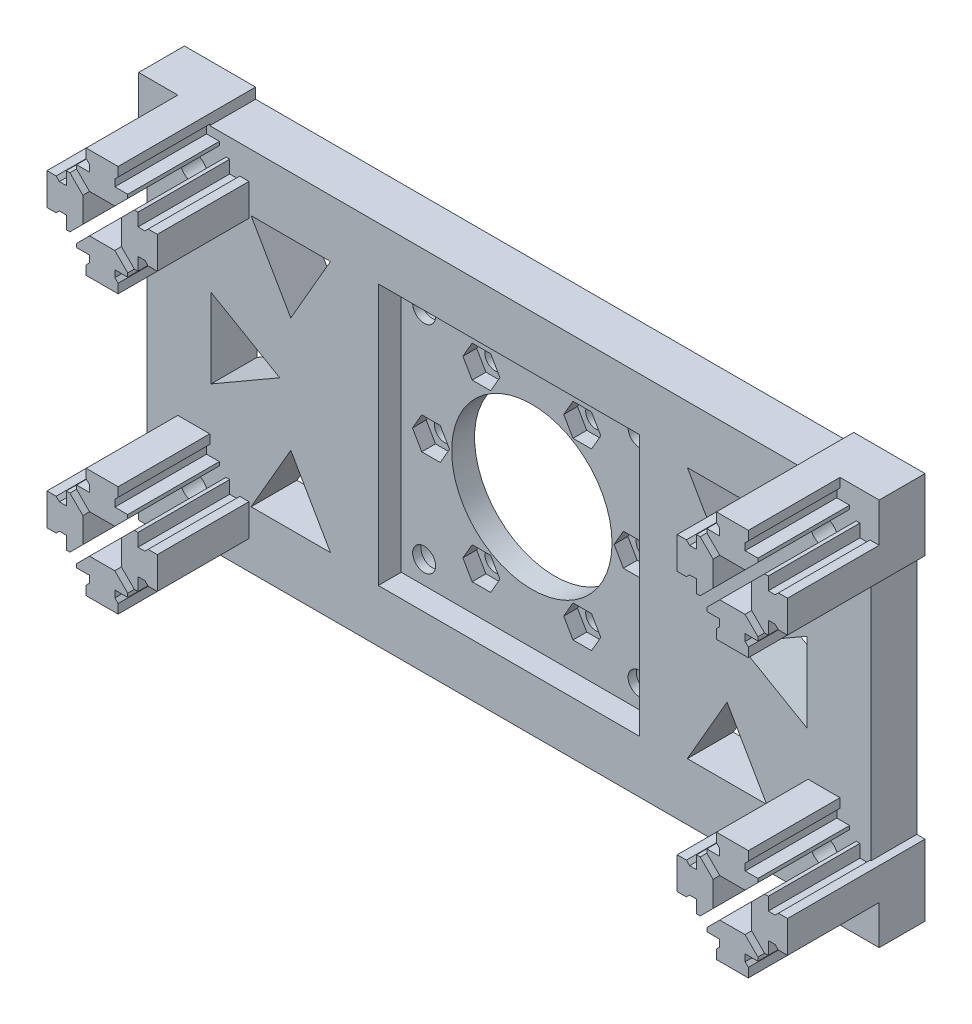
SolidWorks part; units mm, degrees
ref_plane "Plan de face" through (0, 0, 0) normal (0, 0, 1) x (1, 0, 0)
ref_plane "Plan de dessus" through (0, 0, 0) normal (0, 1, 0) x (1, 0, 0)
ref_plane "Plan de droite" through (0, 0, 0) normal (1, 0, 0) x (0, 0, -1)
sketch "Esquisse1" plane through (0, 0, 0) normal (0, 0, 1) x (1, 0, 0)
  line L0 (0, 0) -> (22, 0) construction
  line L1 (0, 0) -> (11, -19.0526) construction
  line L2 (0, 0) -> (-11, -19.0526) construction
  line L3 (0, 0) -> (-22, 0) construction
  line L4 (0, 0) -> (-11, 19.0526) construction
  line L5 (0, 0) -> (11, 19.0526) construction
  line L6 (-23.5, 21.05) -> (-23.5, 23.55)
  line L7 (23.5, -23.55) -> (21, -23.55)
  line L8 (23.5, -23.55) -> (23.5, -21.05)
  line L9 (23.5, 23.55) -> (21, 23.55)
  line L10 (-23.5, -23.55) -> (-23.5, -21.05)
  line L11 (23.5, -23.55) -> (-23.5, 23.55) construction
  line L12 (23.5, 23.55) -> (-23.5, -23.55) construction
  line L13 (-21, 23.55) -> (-23.5, 23.55)
  line L14 (23.5, 21.05) -> (23.5, 23.55)
  line L15 (-21, -23.55) -> (-23.5, -23.55)
  line L17 (79, -40) -> (-79, -40)
  line L18 (79, -40) -> (79, 40)
  line L19 (79, 40) -> (-79, 40)
  line L20 (-79, -40) -> (-79, 40)
  line L21 (79, -40) -> (-79, 40) construction
  line L22 (79, 40) -> (-79, -40) construction
  circle A0 centre (22, 0) radius 2.25
  circle A1 centre (11, -19.0526) radius 2.25
  circle A2 centre (-11, -19.0526) radius 2.25
  circle A3 centre (-22, 0) radius 2.25
  circle A4 centre (-11, 19.0526) radius 2.25
  circle A5 centre (11, 19.0526) radius 2.25
  circle A6 centre (-23.5, 23.55) radius 2.5
  circle A7 centre (23.5, 23.55) radius 2.5
  circle A8 centre (23.5, -23.55) radius 2.5
  circle A9 centre (-23.5, -23.55) radius 2.5
  circle A11 centre (0, 0) radius 17.5
  point P17 (0, 0)
  dimension "D5" = 4.5
  dimension "D6" = 5
  dimension "D7" = 5
  dimension "D8" = 5
  dimension "D9" = 5
  dimension "D11" = 35
  dimension "D1" = 22
  dimension "D3" = 47
  dimension "D4" = 47.1
  dimension "D12" = 80
  dimension "D13" = 158
  dimension "D2" = 6
extrude "Boss.-Extru.1" add sketch "Esquisse1" along normal blind 10
sketch "Esquisse2" plane through (0, 0, 0) normal (0, 0, -1) x (-1, 0, 0)
  line L0 (-68.755, 30.26) -> (-68.755, -30.0028) construction
  circle A0 centre (68.755, 30.26) radius 3
  circle A1 centre (-68.755, 30.26) radius 3
  circle A3 centre (68.755, -30.0028) radius 3
  circle A4 centre (-68.755, -30.0028) radius 3
  dimension "D1" = 6
  dimension "D2" = 6
  dimension "D3" = 6
  dimension "D4" = 6
extrude "Enlèv. mat.-Extru.1" cut sketch "Esquisse2" against normal blind 10
sketch "Esquisse3" plane through (0, 0, 10) normal (0, 0, 1) x (1, 0, 0)
  line L0 (-47.595, -12.5) -> (-47.595, 12.5) construction
  line L1 (79, 40) -> (-79, 40) construction
  line L3 (0, 0) -> (0, 40) construction
  line L12 (-47.595, 12.5) -> (-38.9348, 27.5)
  line L24 (-38.9348, 27.5) -> (-56.2553, 27.5)
  line L28 (-56.2553, 27.5) -> (-47.595, 12.5)
  line L29 (0, 0) -> (-50, 0) construction
  line L30 (-50, 0) -> (-65, 8.6603)
  line L31 (-65, 8.6603) -> (-65, -8.6603)
  line L32 (-65, -8.6603) -> (-50, 0)
  line L33 (-47.595, -12.5) -> (-56.2553, -27.5)
  line L34 (-56.2553, -27.5) -> (-38.9348, -27.5)
  line L35 (-38.9348, -27.5) -> (-47.595, -12.5)
  line L36 (56.2553, -27.5) -> (38.9348, -27.5)
  line L37 (47.595, -12.5) -> (56.2553, -27.5)
  line L38 (38.9348, -27.5) -> (47.595, -12.5)
  line L39 (65, 8.6603) -> (65, -8.6603)
  line L40 (50, 0) -> (65, 8.6603)
  line L41 (65, -8.6603) -> (50, 0)
  line L42 (38.9348, 27.5) -> (56.2553, 27.5)
  line L43 (47.595, 12.5) -> (38.9348, 27.5)
  line L44 (56.2553, 27.5) -> (47.595, 12.5)
  point P5 (-47.595, 0)
  dimension "D1" = 25
  dimension "D2" = 50
  dimension "D3" = 15
  dimension "D4" = 15
  dimension "D5" = 15
extrude "Enlèv. mat.-Extru.3" cut sketch "Esquisse3" against normal blind 10
sketch "Esquisse5" plane through (0, 0, 10) normal (0, 0, 1) x (1, 0, 0)
  line L1 (28.5, -28.5) -> (-28.5, -28.5)
  line L2 (28.5, -28.5) -> (28.5, 28.5)
  line L3 (28.5, 28.5) -> (-28.5, 28.5)
  line L4 (-28.5, -28.5) -> (-28.5, 28.5)
  line L5 (28.5, -28.5) -> (-28.5, 28.5) construction
  line L6 (28.5, 28.5) -> (-28.5, -28.5) construction
  point P0 (0, 0)
  dimension "D1" = 57
  dimension "D2" = 57
extrude "Enlèv. mat.-Extru.4" cut sketch "Esquisse5" against normal blind 5
sketch "Esquisse6" plane through (0, 0, 5) normal (0, 0, 1) x (1, 0, 0)
  line L0 (13.0207, 15.5526) -> (15.0415, 19.0526)
  line L1 (-6.9585, 19.0526) -> (-8.9793, 22.5526)
  line L2 (-8.9793, 22.5526) -> (-13.0207, 22.5526)
  line L3 (-13.0207, 22.5526) -> (-15.0415, 19.0526)
  line L4 (-15.0415, 19.0526) -> (-13.0207, 15.5526)
  line L5 (-13.0207, 15.5526) -> (-8.9793, 15.5526)
  line L6 (-8.9793, 15.5526) -> (-6.9585, 19.0526)
  line L7 (15.0415, 19.0526) -> (13.0207, 22.5526)
  line L8 (13.0207, 22.5526) -> (8.9793, 22.5526)
  line L9 (8.9793, 22.5526) -> (6.9585, 19.0526)
  line L10 (6.9585, 19.0526) -> (8.9793, 15.5526)
  line L11 (8.9793, 15.5526) -> (13.0207, 15.5526)
  line L12 (19.9793, -3.5) -> (24.0207, -3.5)
  line L13 (24.0207, -3.5) -> (26.0415, 0)
  line L14 (26.0415, 0) -> (24.0207, 3.5)
  line L15 (24.0207, 3.5) -> (19.9793, 3.5)
  line L16 (19.9793, 3.5) -> (17.9585, 0)
  line L17 (17.9585, 0) -> (19.9793, -3.5)
  line L18 (6.9585, -19.0526) -> (8.9793, -22.5526)
  line L19 (8.9793, -22.5526) -> (13.0207, -22.5526)
  line L20 (13.0207, -22.5526) -> (15.0415, -19.0526)
  line L21 (15.0415, -19.0526) -> (13.0207, -15.5526)
  line L22 (13.0207, -15.5526) -> (8.9793, -15.5526)
  line L23 (8.9793, -15.5526) -> (6.9585, -19.0526)
  line L24 (-13.0207, -15.5526) -> (-15.0415, -19.0526)
  line L25 (-15.0415, -19.0526) -> (-13.0207, -22.5526)
  line L26 (-13.0207, -22.5526) -> (-8.9793, -22.5526)
  line L27 (-8.9793, -22.5526) -> (-6.9585, -19.0526)
  line L28 (-6.9585, -19.0526) -> (-8.9793, -15.5526)
  line L29 (-8.9793, -15.5526) -> (-13.0207, -15.5526)
  line L30 (-19.9793, 3.5) -> (-24.0207, 3.5)
  line L31 (-24.0207, 3.5) -> (-26.0415, 0)
  line L32 (-26.0415, 0) -> (-24.0207, -3.5)
  line L33 (-24.0207, -3.5) -> (-19.9793, -3.5)
  line L34 (-19.9793, -3.5) -> (-17.9585, 0)
  line L35 (-17.9585, 0) -> (-19.9793, 3.5)
  circle A0 centre (-11, 19.0526) radius 3.5 construction
  point P41 (0, 0)
  dimension "D1" = 3.5
  dimension "D2" = 6
extrude "Enlèv. mat.-Extru.5" cut sketch "Esquisse6" against normal blind 3
sketch "Esquisse8" plane through (0, 0, 10) normal (0, 0, 1) x (1, 0, 0)
  line L0 (-60.0442, 30.26) -> (-68.755, 30.26) construction
  line L5 (-58.9319, 20.3201) -> (-78.6956, 40.3187) construction
  line L6 (-58.6956, 40.3187) -> (-78.8144, 20.2013) construction
  line L7 (-64.555, 27.51) -> (-64.555, 33.01)
  line L8 (-64.555, 33.01) -> (-61.7266, 35.8384)
  line L9 (-61.7266, 35.8384) -> (-60.9266, 35.8384)
  line L10 (-60.9266, 35.8384) -> (-60.9266, 33.0384)
  line L11 (-60.9266, 33.0384) -> (-59.4266, 33.0384)
  line L12 (-59.4266, 33.0384) -> (-58.7195, 33.7455)
  line L13 (-65.9766, 20.9316) -> (-65.2695, 20.2245)
  line L14 (-58.7195, 33.7455) -> (-56.7195, 33.7455)
  line L15 (-60.9266, 27.4816) -> (-59.4266, 27.4816)
  line L16 (-59.4266, 27.4816) -> (-58.7195, 26.7745)
  line L17 (-60.9266, 24.6816) -> (-60.9266, 27.4816)
  line L18 (-61.7266, 24.6816) -> (-60.9266, 24.6816)
  line L19 (-64.555, 27.51) -> (-61.7266, 24.6816)
  line L22 (-58.7195, 26.7745) -> (-56.7195, 26.7745)
  line L23 (-56.7195, 33.7455) -> (-56.7195, 26.7745)
  line L24 (-58.7195, 33.7455) -> (-56.7195, 26.7745) construction
  line L25 (-58.7195, 26.7745) -> (-56.7195, 33.7455) construction
  line L26 (-65.2695, 20.2245) -> (-65.2695, 18.2245)
  line L27 (-65.2695, 18.2245) -> (-72.2405, 18.2245)
  line L28 (-72.2405, 20.2245) -> (-72.2405, 18.2245)
  line L29 (-71.5334, 20.9316) -> (-72.2405, 20.2245)
  line L30 (-71.5334, 22.4316) -> (-71.5334, 20.9316)
  line L31 (-74.3334, 22.4316) -> (-71.5334, 22.4316)
  line L32 (-74.3334, 23.2316) -> (-74.3334, 22.4316)
  line L33 (-71.505, 26.06) -> (-74.3334, 23.2316)
  line L34 (-71.505, 26.06) -> (-66.005, 26.06)
  line L35 (-66.005, 26.06) -> (-63.1766, 23.2316)
  line L36 (-63.1766, 23.2316) -> (-63.1766, 22.4316)
  line L37 (-63.1766, 22.4316) -> (-65.9766, 22.4316)
  line L38 (-65.9766, 22.4316) -> (-65.9766, 20.9316)
  line L39 (-78.0834, 27.4816) -> (-78.7905, 26.7745)
  line L40 (-78.7905, 26.7745) -> (-80.7905, 26.7745)
  line L41 (-80.7905, 26.7745) -> (-80.7905, 33.7455)
  line L42 (-78.7905, 33.7455) -> (-80.7905, 33.7455)
  line L43 (-78.0834, 33.0384) -> (-78.7905, 33.7455)
  line L44 (-76.5834, 33.0384) -> (-78.0834, 33.0384)
  line L45 (-76.5834, 35.8384) -> (-76.5834, 33.0384)
  line L46 (-75.7834, 35.8384) -> (-76.5834, 35.8384)
  line L47 (-72.955, 33.01) -> (-75.7834, 35.8384)
  line L48 (-72.955, 33.01) -> (-72.955, 27.51)
  line L49 (-72.955, 27.51) -> (-75.7834, 24.6816)
  line L50 (-75.7834, 24.6816) -> (-76.5834, 24.6816)
  line L51 (-76.5834, 24.6816) -> (-76.5834, 27.4816)
  line L52 (-76.5834, 27.4816) -> (-78.0834, 27.4816)
  line L53 (-71.5334, 39.5884) -> (-72.2405, 40.2955)
  line L54 (-72.2405, 40.2955) -> (-72.2405, 42.2955)
  line L55 (-72.2405, 42.2955) -> (-65.2695, 42.2955)
  line L56 (-65.2695, 40.2955) -> (-65.2695, 42.2955)
  line L57 (-65.9766, 39.5884) -> (-65.2695, 40.2955)
  line L58 (-65.9766, 38.0884) -> (-65.9766, 39.5884)
  line L59 (-63.1766, 38.0884) -> (-65.9766, 38.0884)
  line L60 (-63.1766, 37.2884) -> (-63.1766, 38.0884)
  line L61 (-66.005, 34.46) -> (-63.1766, 37.2884)
  line L62 (-66.005, 34.46) -> (-71.505, 34.46)
  line L63 (-71.505, 34.46) -> (-74.3334, 37.2884)
  line L64 (-74.3334, 37.2884) -> (-74.3334, 38.0884)
  line L65 (-74.3334, 38.0884) -> (-71.5334, 38.0884)
  line L66 (-71.5334, 38.0884) -> (-71.5334, 39.5884)
  point P0 (-68.755, 30.26)
  point P11 (-64.555, 30.26)
  point P23 (-57.7195, 30.26)
  dimension "D1" = 20
  dimension "D2" = 20
  dimension "D3" = 5.5
  dimension "D4" = 4
  dimension "D5" = 0.8
  dimension "D6" = 2.8
  dimension "D7" = 1.5
  dimension "D8" = 1
  dimension "D9" = 135
  dimension "D10" = 135
  dimension "D11" = 2
  dimension "D12" = 6.9711
  dimension "D14" = 4.2
  dimension "D13" = 4
extrude "Boss.-Extru.2" add sketch "Esquisse8" along normal blind 20
pattern_circular "Répétition circulaire1" count 2 over 360 about axis through (0, 0, 0) along (0, 0, 1) of "Boss.-Extru.2"
sketch "Esquisse9" plane through (0, 0, 10) normal (0, 0, 1) x (1, 0, 0)
  line L0 (0, 0) -> (11.1513, 0) construction
ref_plane "Plan1" through (0, 0, 0) normal (0, -1, 0) x (1, 0, 0)
mirror "Symétrie1" about plane through (0, 0, 0) normal (0, -1, 0) of "Boss.-Extru.2"
mirror "Symétrie2" about plane through (0, 0, 0) normal (0, -1, 0) of "Répétition circulaire1"
sketch "Esquisse11" plane through (0, 0, 0) normal (0, 0, -1) x (-1, 0, 0)
  line L0 (-79, 40) -> (79, 40) construction
  line L1 (65.2695, 42.2955) -> (72.3097, 42.2955)
  line L2 (65.2695, 42.2955) -> (65.2695, 40)
  line L3 (65.2695, 40) -> (72.3097, 40)
  line L5 (65.2695, 42.2955) -> (72.3097, 40) construction
  line L6 (65.2695, 40) -> (72.3097, 42.2955) construction
  line L7 (-79, -40) -> (79, -40) construction
  line L9 (80.7905, 33.7455) -> (80.7905, 26.7745)
  line L10 (80.7905, 26.7745) -> (79, 26.7745)
  line L11 (79, 33.7455) -> (79, 26.7745)
  line L12 (80.7905, 33.7455) -> (79, 26.7745) construction
  line L13 (80.7905, 26.7745) -> (79, 33.7455) construction
  line L14 (72.3097, 42.2955) -> (80.7905, 42.2955)
  line L15 (72.3097, 40) -> (72.3097, 33.7455)
  line L16 (72.3097, 33.7455) -> (79, 33.7455)
  line L17 (80.7905, 42.2955) -> (80.7905, 33.7455)
  line L18 (72.3097, 42.2955) -> (80.7905, 33.7455) construction
  line L19 (72.3097, 33.7455) -> (80.7905, 42.2955) construction
  line L20 (65.2695, -42.2955) -> (72.2405, -42.2955)
  line L21 (65.2695, -42.2955) -> (65.2695, -40)
  line L22 (65.2695, -40) -> (72.2405, -40)
  line L24 (65.2695, -42.2955) -> (72.2405, -40) construction
  line L25 (65.2695, -40) -> (72.2405, -42.2955) construction
  line L27 (80.7905, -26.7745) -> (79, -26.7745)
  line L28 (80.7905, -26.7745) -> (80.7905, -33.7455)
  line L30 (79, -26.7745) -> (79, -33.7455)
  line L31 (80.7905, -26.7745) -> (79, -33.7455) construction
  line L32 (80.7905, -33.7455) -> (79, -26.7745) construction
  line L33 (79, -33.7455) -> (72.2405, -33.7455)
  line L34 (80.7905, -33.7455) -> (80.7905, -42.2955)
  line L35 (80.7905, -42.2955) -> (72.2405, -42.2955)
  line L36 (72.2405, -33.7455) -> (72.2405, -40)
  line L37 (80.7905, -33.7455) -> (72.2405, -42.2955) construction
  line L38 (80.7905, -42.2955) -> (72.2405, -33.7455) construction
  line L39 (-80.7905, -26.7745) -> (-79, -26.7745)
  line L40 (-80.7905, -26.7745) -> (-80.7905, -33.7455)
  line L42 (-79, -26.7745) -> (-79, -33.7455)
  line L43 (-80.7905, -26.7745) -> (-79, -33.7455) construction
  line L44 (-80.7905, -33.7455) -> (-79, -26.7745) construction
  line L45 (-72.2405, -42.2955) -> (-65.2405, -42.2955)
  line L47 (-72.2405, -40) -> (-65.2405, -40)
  line L48 (-65.2405, -42.2955) -> (-65.2405, -40)
  line L49 (-72.2405, -42.2955) -> (-65.2405, -40) construction
  line L50 (-72.2405, -40) -> (-65.2405, -42.2955) construction
  line L51 (-79, -33.7455) -> (-72.2405, -33.7455)
  line L52 (-80.7905, -33.7455) -> (-80.7905, -42.2955)
  line L53 (-80.7905, -42.2955) -> (-72.2405, -42.2955)
  line L54 (-72.2405, -33.7455) -> (-72.2405, -40)
  line L55 (-80.7905, -33.7455) -> (-72.2405, -42.2955) construction
  line L56 (-80.7905, -42.2955) -> (-72.2405, -33.7455) construction
  line L57 (-72.2405, 42.2955) -> (-65.2405, 42.2955)
  line L59 (-72.2405, 40) -> (-65.2405, 40)
  line L60 (-65.2405, 42.2955) -> (-65.2405, 40)
  line L61 (-72.2405, 42.2955) -> (-65.2405, 40) construction
  line L62 (-72.2405, 40) -> (-65.2405, 42.2955) construction
  line L64 (-80.7905, 33.7455) -> (-80.7905, 26.7745)
  line L65 (-80.7905, 26.7745) -> (-79, 26.7745)
  line L66 (-79, 33.7455) -> (-79, 26.7745)
  line L67 (-80.7905, 33.7455) -> (-79, 26.7745) construction
  line L68 (-80.7905, 26.7745) -> (-79, 33.7455) construction
  line L69 (-79, 33.7455) -> (-72.2405, 33.7455)
  line L70 (-80.7905, 33.7455) -> (-80.7905, 42.2955)
  line L71 (-80.7905, 42.2955) -> (-72.2405, 42.2955)
  line L72 (-72.2405, 33.7455) -> (-72.2405, 40)
  line L73 (-80.7905, 33.7455) -> (-72.2405, 42.2955) construction
  line L74 (-80.7905, 42.2955) -> (-72.2405, 33.7455) construction
  point P4 (68.7896, 41.1478)
  point P12 (79.8953, 30.26)
  point P18 (76.5501, 38.0205)
  point P22 (68.755, -41.1478)
  point P30 (79.8953, -30.26)
  point P36 (76.5155, -38.0205)
  point P40 (-79.8953, -30.26)
  point P47 (-68.7405, -41.1478)
  point P52 (-76.5155, -38.0205)
  point P56 (-68.7405, 41.1478)
  point P62 (-79.8953, 30.26)
  point P68 (-76.5155, 38.0205)
  dimension "D1" = 7
extrude "Boss.-Extru.3" add sketch "Esquisse11" against normal up to surface (10 mm away) up to face at (0, 0, 10)
sketch "Esquisse12" plane through (0, 0, 0) normal (0, 0, -1) x (-1, 0, 0)
  line L0 (-46.5251, 0) -> (46.5251, 0) construction
  line L1 (0, 0) -> (0, 13.1803) construction
  circle A0 centre (-23.5, 23.55) radius 4.25
  circle A1 centre (23.55, 23.5) radius 4.25
  circle A2 centre (23.5, -23.55) radius 4.25
  circle A3 centre (-23.55, -23.5) radius 4.25
  circle A4 centre (-68.755, 30.26) radius 5.5
  circle A5 centre (-68.755, -30.26) radius 5.5
  circle A6 centre (68.755, -30.26) radius 5.5
  circle A7 centre (68.755, 30.26) radius 5.5
  point P12 (0, 0)
  dimension "D1" = 8.5
  dimension "D3" = 11
  dimension "D2" = 4
extrude "Enlèv. mat.-Extru.6" cut sketch "Esquisse12" against normal blind 3.2
